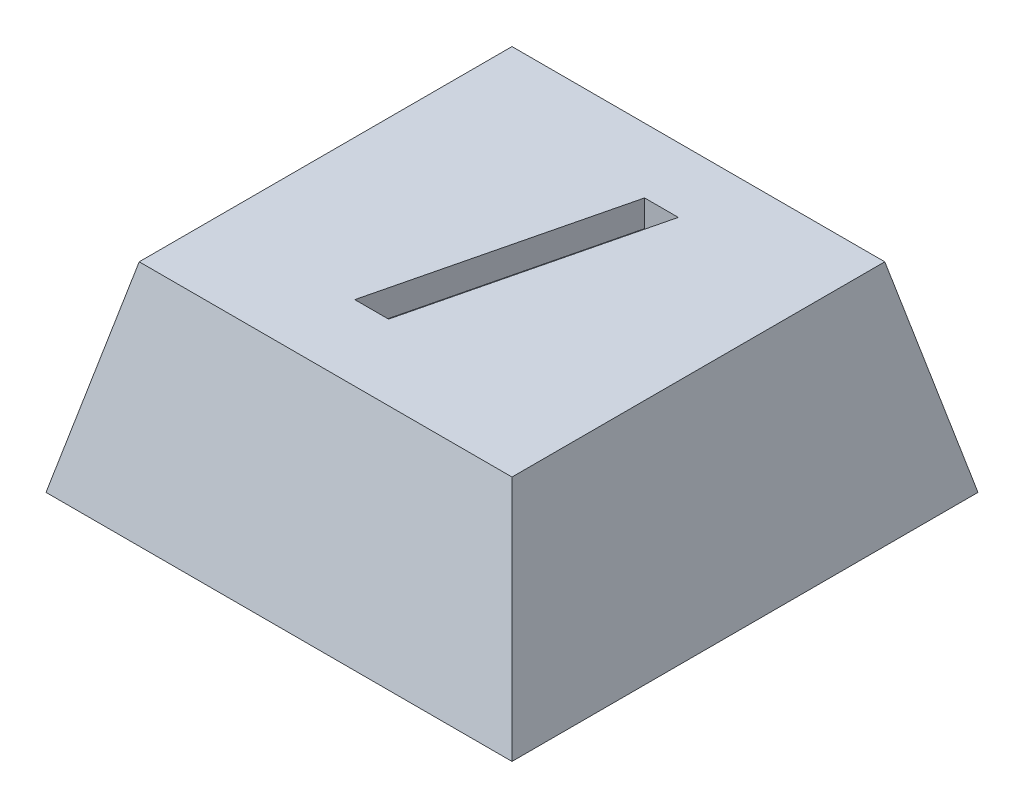
SolidWorks part; units mm, degrees
ref_plane "Front Plane" through (0, 0, 0) normal (0, 0, 1) x (1, 0, 0)
ref_plane "Top Plane" through (0, 0, 0) normal (0, 1, 0) x (1, 0, 0)
ref_plane "Right Plane" through (0, 0, 0) normal (1, 0, 0) x (0, 0, -1)
sketch "Sketch1" plane through (0, 0, 0) normal (0, 1, 0) x (1, 0, 0)
  line L1 (0, 0) -> (7, 0)
  line L2 (0, 0) -> (0, 7)
  line L3 (0, 7) -> (7, 7)
  line L4 (7, 0) -> (7, 7)
  dimension "D1" = 7
  dimension "D2" = 7
extrude "Boss-Extrude1" add sketch "Sketch1" along normal blind 3
sketch "Sketch2" plane through (0, 0, 0) normal (0, 0, 1) x (1, 0, 0)
  line L0 (0, 0) -> (0.7, 3)
  line L1 (0, 3) -> (7, 3) construction
  line L2 (0.7, 3) -> (0, 3)
  line L3 (0, 3) -> (0, 0)
  line L4 (7, 0) -> (6.3, 3)
  line L5 (6.3, 3) -> (7, 3)
  line L6 (7, 3) -> (7, 0)
  dimension "D1" = 0.7
  dimension "D2" = 0.7
extrude "Cut-Extrude1" cut sketch "Sketch2" against normal blind 7
sketch "Sketch3" plane through (0, 0, 0) normal (1, 0, 0) x (0, 0, -1)
  line L0 (0, 0) -> (0.7, 3)
  line L1 (7, 3) -> (0, 3) construction
  line L2 (0.7, 3) -> (0, 3)
  line L3 (0, 3) -> (0, 0)
  line L4 (7, 3) -> (6.3, 3)
  line L5 (6.3, 3) -> (7, 0)
  line L6 (7, 3) -> (7, 0)
  dimension "D1" = 0.7
  dimension "D2" = 0.7
extrude "Cut-Extrude2" cut sketch "Sketch3" along normal blind 11
sketch "Sketch4" plane through (0, 0, 0) normal (0, -1, 0) x (1, 0, 0)
  line L0 (3.5, 0) -> (3.5, -7) construction
  line L1 (0, 0) -> (7, 0) construction
  line L2 (7, -7) -> (0, -7) construction
  line L3 (0, -3.5) -> (7, -3.5) construction
  line L4 (0, -7) -> (0, 0) construction
  line L5 (7, 0) -> (7, -7) construction
  circle A0 centre (3.5, -3.5) radius 1.8
  dimension "D1" = 3.6
extrude "Cut-Extrude3" cut sketch "Sketch4" against normal blind 0.8
sketch "Sketch6" plane through (0, 3, 0) normal (0, 1, 0) x (1, 0, 0)
  text T0 "/" font "Arial" height 3.5
extrude "Cut-Extrude4" cut sketch "Sketch6" against normal blind 0.4
